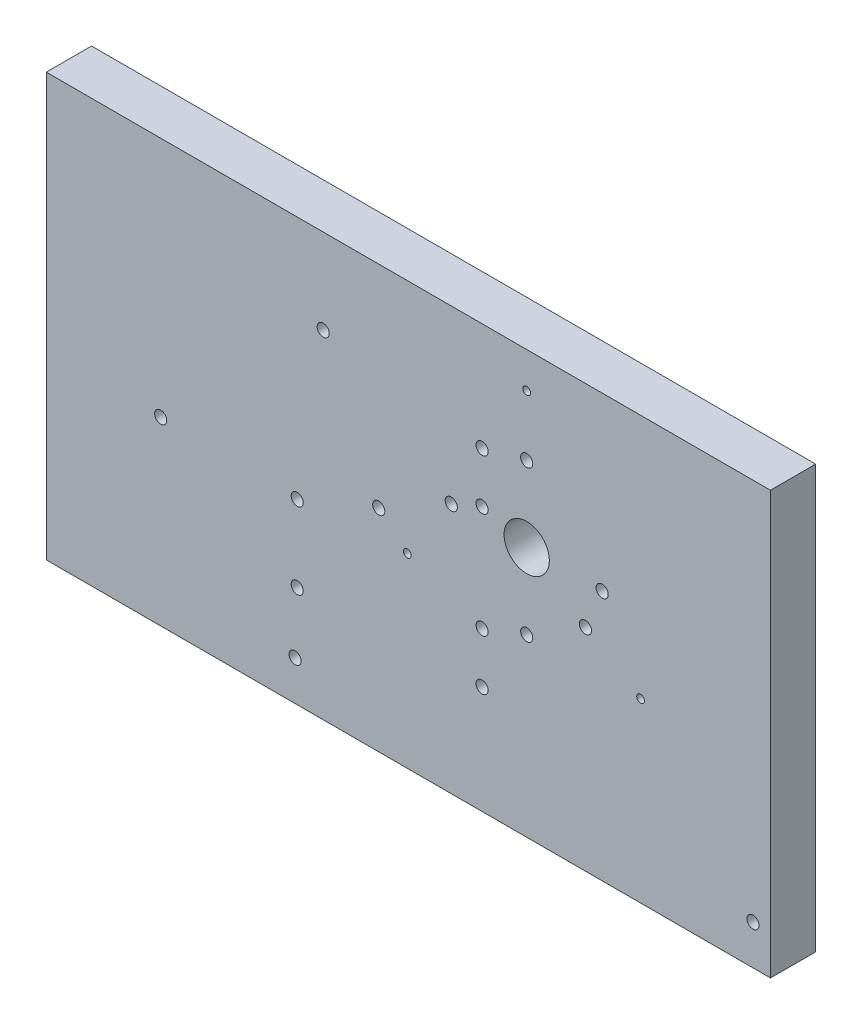
SolidWorks part; units mm, degrees
ref_plane "Front Plane" through (0, 0, 0) normal (0, 0, 1) x (1, 0, 0)
ref_plane "Top Plane" through (0, 0, 0) normal (0, 1, 0) x (1, 0, 0)
ref_plane "Right Plane" through (0, 0, 0) normal (1, 0, 0) x (0, 0, -1)
sketch "Sketch1" plane through (0, 0, 0) normal (0, 0, 1) x (1, 0, 0)
  line L1 (-152.4, -88.9) -> (152.4, -88.9)
  line L2 (-152.4, -88.9) -> (-152.4, 88.9)
  line L3 (-152.4, 88.9) -> (152.4, 88.9)
  line L4 (152.4, -88.9) -> (152.4, 88.9)
  line L5 (-152.4, -88.9) -> (152.4, 88.9) construction
  line L6 (-152.4, 88.9) -> (152.4, -88.9) construction
  point P0 (0, 0)
  dimension "D1" = 304.8
  dimension "D2" = 177.8
extrude "Boss-Extrude1" add sketch "Sketch1" against normal blind 19.05
sketch "Sketch2" plane through (0, 0, 0) normal (0, 0, 1) x (1, 0, 0)
  line L0 (18.0555, 16.7132) -> (81.5555, 16.7132) construction
  line L1 (49.8055, 48.4632) -> (49.8055, -15.0368) construction
  circle A1 centre (-104.2487, -12.7585) radius 2.5527
  circle A2 centre (-104.2487, -12.7585) radius 2.5527
  circle A3 centre (-46.7932, -46.1745) radius 2.5527
  circle A4 centre (-46.7932, -46.1745) radius 2.5527
  circle A5 centre (18.0555, 16.7132) radius 2.5527
  circle A6 centre (18.0555, 16.7132) radius 2.5527
  circle A7 centre (-35.8518, 53.1355) radius 2.5527
  circle A8 centre (-35.8518, 53.1355) radius 2.5527
  circle A9 centre (-47.6939, -72.1868) radius 2.5527
  circle A10 centre (-47.6939, -72.1868) radius 2.5527
  circle A11 centre (49.8055, 48.4632) radius 2.5527
  circle A12 centre (49.8055, 48.4632) radius 2.5527
  circle A13 centre (81.5555, 16.7132) radius 2.5527
  circle A14 centre (81.5555, 16.7132) radius 2.5527
  circle A15 centre (49.8055, -15.0368) radius 2.5527
  circle A16 centre (49.8055, -15.0368) radius 2.5527
  circle A17 centre (-46.7932, -14.0022) radius 2.5527
  circle A18 centre (-46.7932, -14.0022) radius 2.5527
  circle A19 centre (49.8055, 73.8632) radius 1.6319
  circle A20 centre (49.8055, 73.8632) radius 1.6319
  circle A21 centre (145.0555, -72.1868) radius 2.5527
  circle A22 centre (145.0555, -72.1868) radius 2.5527
  circle A23 centre (-0.4188, -10.5564) radius 1.6319
  circle A24 centre (-0.4188, -10.5564) radius 1.6319
  circle A25 centre (97.7356, -14.4129) radius 1.6319
  circle A26 centre (97.7356, -14.4129) radius 1.6319
  circle A52 centre (49.8055, 16.7132) radius 9.525
  dimension "D14" = 19.05
  dimension "D1" = 0
  dimension "D2" = 0
  dimension "D3" = 0
  dimension "D4" = 0
  dimension "D5" = 0
  dimension "D6" = 0
  dimension "D7" = 0
  dimension "D8" = 0
  dimension "D9" = 0
  dimension "D10" = 0
  dimension "D11" = 0
  dimension "D12" = 0
  dimension "D13" = 0
extrude "Cut-Extrude1" cut sketch "Sketch2" against normal through all
sketch "Sketch10" plane through (0, 0, 0) normal (0, 0, 1) x (1, 0, 0)
  line L0 (12.2467, 16.7132) -> (31.0261, 0) construction
  line L1 (31.0261, 43.5) -> (31.0261, 22.225) construction
  line L2 (31.0261, 22.225) -> (31.0261, 0) construction
  line L3 (31.0261, 0) -> (74.5261, 0) construction
  line L4 (31.0261, -43.5) -> (31.0261, -22.225) construction
  line L5 (31.0261, -22.225) -> (31.0261, 0) construction
  line L6 (31.0261, 0) -> (-12.4739, 0) construction
  line L7 (31.0261, 43.5) -> (31.0261, 88.9) construction
  line L8 (-12.4739, 0) -> (-90.3478, 0) construction
  line L9 (49.8055, 16.7132) -> (31.0261, 0) construction
  line L10 (74.5261, 0) -> (152.4, 0) construction
  line L11 (152.4, -88.9) -> (152.4, 88.9) construction
  line L12 (152.4, 88.9) -> (-152.4, 88.9) construction
  circle A0 centre (31.0261, -43.5) radius 2.5527
  circle A1 centre (-12.4739, 0) radius 2.5527
  circle A2 centre (31.0261, 43.5) radius 2.5527
  circle A3 centre (74.5261, 0) radius 2.5527
  circle A4 centre (31.0261, -22.225) radius 2.5527
  circle A5 centre (31.0261, 0) radius 9.525
  circle A6 centre (31.0261, 22.225) radius 2.5527
  point P19 (0, 0)
  point P20 (181.7748, -49.056)
  dimension "D1" = 5.1054
  dimension "D2" = 45.4
  dimension "D3" = 21.275
  dimension "D4" = 22.225
  dimension "D5" = 43.5
  dimension "D6" = 77.8739
  dimension "D7" = 25.1396
  dimension "D8" = 41.668
extrude "Cut-Extrude2" cut sketch "Sketch10" against normal through all contours A1 | A0 | A3 | A2 | A6 | A4
